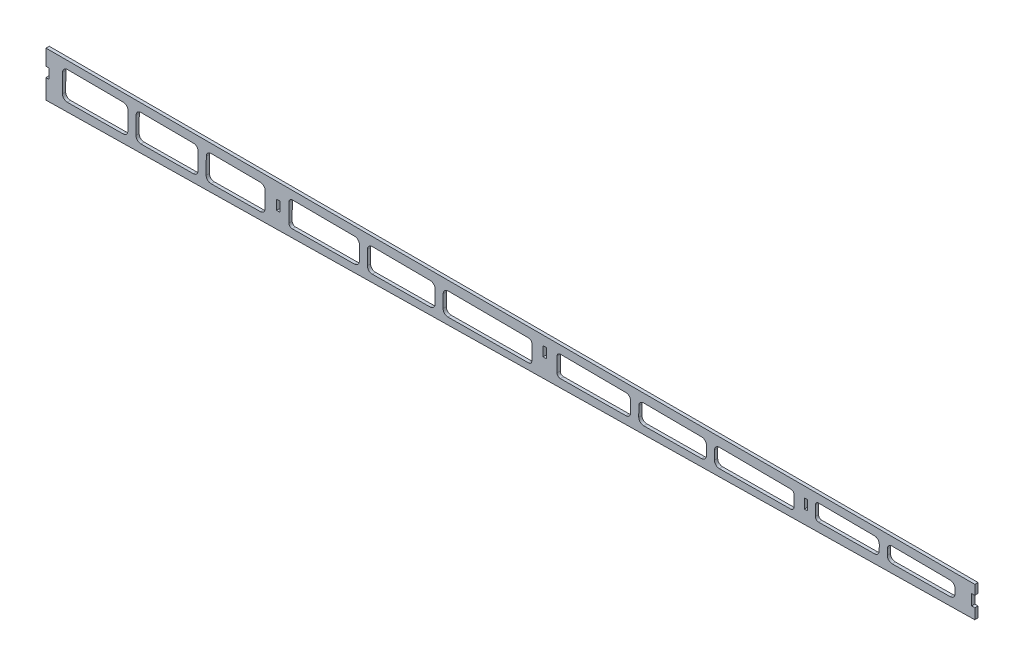
SolidWorks part; units mm, degrees
ref_plane "前视基准面" through (0, 0, 0) normal (0, 0, 1) x (1, 0, 0)
ref_plane "上视基准面" through (0, 0, 0) normal (0, 1, 0) x (1, 0, 0)
ref_plane "右视基准面" through (0, 0, 0) normal (1, 0, 0) x (0, 0, -1)
sketch "Model" plane through (0, 0, 0) normal (0, 0, 1) x (1, 0, 0)
  line L0 (586.2163, 41.7684) -> (586.2163, 35.8554)
  line L1 (584.2163, 35.8554) -> (584.2163, 29.1549)
  line L2 (584.2163, 29.1549) -> (586.2163, 29.1549)
  line L3 (153.779, 32.1444) -> (153.779, 26.1444)
  line L4 (318.8552, 33.15) -> (318.8552, 30.0955)
  line L5 (480.7142, 34.4585) -> (480.7142, 29.3765)
  line L6 (10.9715, 41.7684) -> (154.8752, 41.7684)
  line L7 (154.8752, 41.7684) -> (317.6526, 41.7684)
  line L8 (317.6526, 41.7684) -> (481.2107, 41.7684)
  line L9 (481.2107, 41.7684) -> (586.2163, 41.7684)
  line L10 (10.9715, 13.8422) -> (586.2163, 22.7505)
  line L11 (584.2163, 35.8554) -> (586.2163, 35.8554)
  line L12 (586.2163, 29.1549) -> (586.2163, 22.7505)
  line L13 (58.7572, 36.7017) -> (24.2578, 36.9107)
  line L14 (58.6999, 19.6377) -> (24.1973, 19.3166)
  line L15 (146.7481, 33.1685) -> (146.689, 23.4105)
  line L16 (21.2397, 33.9289) -> (21.1694, 22.3346)
  line L17 (69.7564, 36.635) -> (102.2558, 36.4381)
  line L18 (69.7001, 19.74) -> (102.2025, 20.0425)
  line L19 (113.2548, 36.3715) -> (143.7663, 36.1867)
  line L20 (113.2026, 20.1449) -> (143.7169, 20.4288)
  line L24 (163.5411, 36.6471) -> (202.0937, 36.4212)
  line L25 (213.0827, 36.3446) -> (248.9947, 36.0944)
  line L26 (259.9844, 36.0179) -> (309.947, 35.7386)
  line L27 (161.5272, 34.6611) -> (161.4469, 23.1264)
  line L28 (163.4655, 21.1126) -> (202.0383, 21.4421)
  line L29 (213.0365, 21.5448) -> (248.9446, 21.8799)
  line L30 (259.9386, 21.9825) -> (309.8865, 22.3787)
  line L31 (311.933, 33.7247) -> (311.8679, 24.3811)
  line L32 (329.5592, 36.8682) -> (370.1439, 36.5855)
  line L33 (381.1437, 36.5089) -> (417.0455, 36.2588)
  line L34 (428.0453, 36.1822) -> (472.3343, 35.8737)
  line L35 (329.5006, 23.7856) -> (370.1137, 24.1846)
  line L36 (381.1131, 24.2872) -> (417.0185, 24.6223)
  line L37 (428.0194, 24.725) -> (472.2921, 25.1383)
  line L38 (327.482, 25.7994) -> (327.5453, 34.8822)
  line L39 (474.3203, 33.8598) -> (474.2734, 27.1242)
  line L40 (489.4811, 36.9709) -> (524.0869, 36.7298)
  line L41 (535.0807, 36.6533) -> (570.9879, 36.4031)
  line L42 (489.4811, 26.7673) -> (524.0687, 27.0901)
  line L43 (535.0669, 27.1927) -> (570.975, 27.5279)
  line L44 (487.4673, 34.9849) -> (487.4625, 28.7687)
  line L45 (10.9715, 25.978) -> (10.9715, 13.8422)
  line L46 (318.8552, 33.15) -> (318.8552, 36.0955)
  line L47 (480.7142, 34.4585) -> (480.7142, 35.3765)
  line L48 (10.9715, 32.0068) -> (12.9715, 32.0068)
  line L49 (12.9715, 32.0068) -> (12.9715, 25.978)
  line L50 (12.9715, 25.978) -> (10.9715, 25.978)
  line L51 (10.9715, 41.7684) -> (10.9715, 32.0068)
  line L52 (153.779, 32.1444) -> (155.779, 32.1444)
  line L53 (155.779, 32.1444) -> (155.779, 26.1444)
  line L54 (155.779, 26.1444) -> (153.779, 26.1444)
  line L55 (318.8552, 36.0955) -> (320.8552, 36.0955)
  line L56 (320.8552, 36.0955) -> (320.8552, 30.0955)
  line L57 (320.8552, 30.0955) -> (318.8552, 30.0955)
  line L58 (480.7142, 35.3765) -> (482.7142, 35.3765)
  line L59 (482.7142, 35.3765) -> (482.7142, 29.3765)
  line L60 (482.7142, 29.3765) -> (480.7142, 29.3765)
  line L61 (573.9669, 33.3823) -> (573.9469, 30.5069)
  line L62 (532.0599, 33.6715) -> (532.0389, 30.2108)
  line L63 (527.0659, 33.709) -> (527.0406, 30.0691)
  line L64 (425.0245, 33.2004) -> (424.9914, 27.7431)
  line L65 (420.0246, 33.2407) -> (419.9904, 27.604)
  line L66 (378.1228, 33.5271) -> (378.0851, 27.3053)
  line L67 (373.1229, 33.5674) -> (373.0841, 27.1662)
  line L68 (256.9635, 33.0361) -> (256.9148, 25.0006)
  line L69 (251.9737, 33.0736) -> (251.9165, 24.8589)
  line L70 (210.0619, 33.3629) -> (210.0085, 24.5628)
  line L71 (205.0727, 33.4003) -> (205.0102, 24.4211)
  line L72 (110.2366, 33.3897) -> (110.1747, 23.1629)
  line L73 (105.2375, 33.42) -> (105.1746, 23.0242)
  line L74 (66.7382, 33.6532) -> (66.6722, 22.7581)
  line L75 (61.7389, 33.6835) -> (61.6719, 22.6194)
  arc A0 (58.6999, 19.6377) -> (61.6719, 22.6194) centre (58.672, 22.6375) ccw
  arc A1 (143.7169, 20.4288) -> (146.689, 23.4105) centre (143.689, 23.4287) ccw
  arc A2 (21.1694, 22.3346) -> (24.1973, 19.3166) centre (24.1694, 22.3165) ccw
  arc A3 (146.7481, 33.1685) -> (143.7663, 36.1867) centre (143.7481, 33.1867) ccw
  arc A4 (24.2578, 36.9107) -> (21.2397, 33.9289) centre (24.2396, 33.9107) ccw
  arc A5 (61.7389, 33.6835) -> (58.7572, 36.7017) centre (58.739, 33.7017) ccw
  arc A6 (69.7564, 36.635) -> (66.7382, 33.6532) centre (69.7382, 33.6351) ccw
  arc A7 (102.2025, 20.0425) -> (105.1746, 23.0242) centre (102.1746, 23.0424) ccw
  arc A8 (105.2375, 33.42) -> (102.2558, 36.4381) centre (102.2376, 33.4382) ccw
  arc A9 (66.6722, 22.7581) -> (69.7001, 19.74) centre (69.6722, 22.7399) ccw
  arc A10 (113.2548, 36.3715) -> (110.2366, 33.3897) centre (113.2366, 33.3716) ccw
  arc A11 (110.1747, 23.1629) -> (113.2026, 20.1449) centre (113.1746, 23.1447) ccw
  arc A12 (163.5411, 36.6471) -> (161.5272, 34.6611) centre (163.5272, 34.6472) ccw
  arc A13 (161.4469, 23.1264) -> (163.4655, 21.1126) centre (163.4468, 23.1125) ccw
  arc A14 (309.8865, 22.3787) -> (311.8679, 24.3811) centre (309.8679, 24.3786) ccw
  arc A15 (205.0727, 33.4003) -> (202.0937, 36.4212) centre (202.0728, 33.4212) ccw
  arc A16 (202.0383, 21.4421) -> (205.0102, 24.4211) centre (202.0103, 24.442) ccw
  arc A17 (213.0827, 36.3446) -> (210.0619, 33.3629) centre (213.0618, 33.3447) ccw
  arc A18 (210.0085, 24.5628) -> (213.0365, 21.5448) centre (213.0085, 24.5446) ccw
  arc A19 (251.9737, 33.0736) -> (248.9947, 36.0944) centre (248.9738, 33.0945) ccw
  arc A20 (248.9446, 21.8799) -> (251.9165, 24.8589) centre (248.9166, 24.8798) ccw
  arc A21 (259.9844, 36.0179) -> (256.9635, 33.0361) centre (259.9635, 33.018) ccw
  arc A22 (256.9148, 25.0006) -> (259.9386, 21.9825) centre (259.9148, 24.9825) ccw
  arc A23 (311.933, 33.7247) -> (309.947, 35.7386) centre (309.9331, 33.7386) ccw
  arc A24 (474.3203, 33.8598) -> (472.3343, 35.8737) centre (472.3204, 33.8737) ccw
  arc A25 (329.5592, 36.8682) -> (327.5453, 34.8822) centre (329.5452, 34.8683) ccw
  arc A26 (327.482, 25.7994) -> (329.5006, 23.7856) centre (329.482, 25.7855) ccw
  arc A27 (472.2921, 25.1383) -> (474.2734, 27.1242) centre (472.2734, 27.1382) ccw
  arc A28 (373.1229, 33.5674) -> (370.1439, 36.5855) centre (370.123, 33.5856) ccw
  arc A29 (370.1137, 24.1846) -> (373.0841, 27.1662) centre (370.0842, 27.1844) ccw
  arc A30 (381.1437, 36.5089) -> (378.1228, 33.5271) centre (381.1228, 33.509) ccw
  arc A31 (378.0851, 27.3053) -> (381.1131, 24.2872) centre (381.0851, 27.2871) ccw
  arc A32 (417.0185, 24.6223) -> (419.9904, 27.604) centre (416.9905, 27.6222) ccw
  arc A33 (420.0246, 33.2407) -> (417.0455, 36.2588) centre (417.0246, 33.2589) ccw
  arc A34 (428.0453, 36.1822) -> (425.0245, 33.2004) centre (428.0245, 33.1823) ccw
  arc A35 (424.9914, 27.7431) -> (428.0194, 24.725) centre (427.9914, 27.7249) ccw
  arc A36 (489.4811, 36.9709) -> (487.4673, 34.9849) centre (489.4672, 34.971) ccw
  arc A37 (487.4625, 28.7687) -> (489.4811, 26.7673) centre (489.4625, 28.7672) ccw
  arc A38 (527.0659, 33.709) -> (524.0869, 36.7298) centre (524.066, 33.7299) ccw
  arc A39 (524.0687, 27.0901) -> (527.0406, 30.0691) centre (524.0407, 30.0899) ccw
  arc A40 (535.0807, 36.6533) -> (532.0599, 33.6715) centre (535.0598, 33.6533) ccw
  arc A41 (532.0389, 30.2108) -> (535.0669, 27.1927) centre (535.0389, 30.1926) ccw
  arc A42 (570.975, 27.5279) -> (573.9469, 30.5069) centre (570.947, 30.5278) ccw
  arc A43 (573.9669, 33.3823) -> (570.9879, 36.4031) centre (570.967, 33.4032) ccw
  point P44 (259.9394, 21.9826)
  point P68 (0, 0)
  point P88 (0, 0)
  point P112 (0, 0)
  point P143 (0, 0)
  point P150 (0, 0)
  point P168 (10.9703, 41.7684)
  point P169 (58.763, 36.7065)
extrude "凸台-拉伸1" add sketch "Model" along normal blind 2
